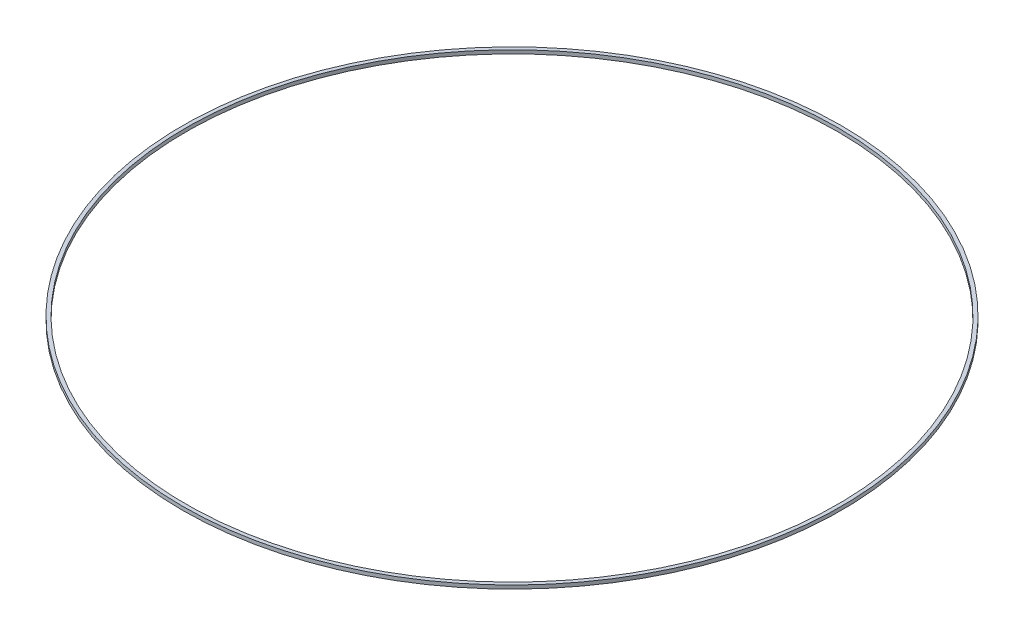
SolidWorks part; units mm, degrees
ref_plane "Front Plane" through (0, 0, 0) normal (0, 0, 1) x (1, 0, 0)
ref_plane "Top Plane" through (0, 0, 0) normal (0, 1, 0) x (1, 0, 0)
ref_plane "Right Plane" through (0, 0, 0) normal (1, 0, 0) x (0, 0, -1)
sketch "Sketch1" plane through (0, 0, 0) normal (0, 0, 1) x (1, 0, 0)
  line L0 (0, 0) -> (0, 3.2414) construction
  line L2 (-194.1686, 0) -> (-196.2899, 0)
  line L3 (-196.2899, 0) -> (-196.2899, 2.1213)
  line L4 (-196.2899, 2.1213) -> (-194.1686, 2.1213)
  line L5 (-194.1686, 2.1213) -> (-194.1686, 0)
  dimension "D1" = 194.1686
  dimension "D2" = 3
  dimension "D3" = 388.3372
revolve "Revolve1" add sketch "Sketch1" angle 360 about L0
